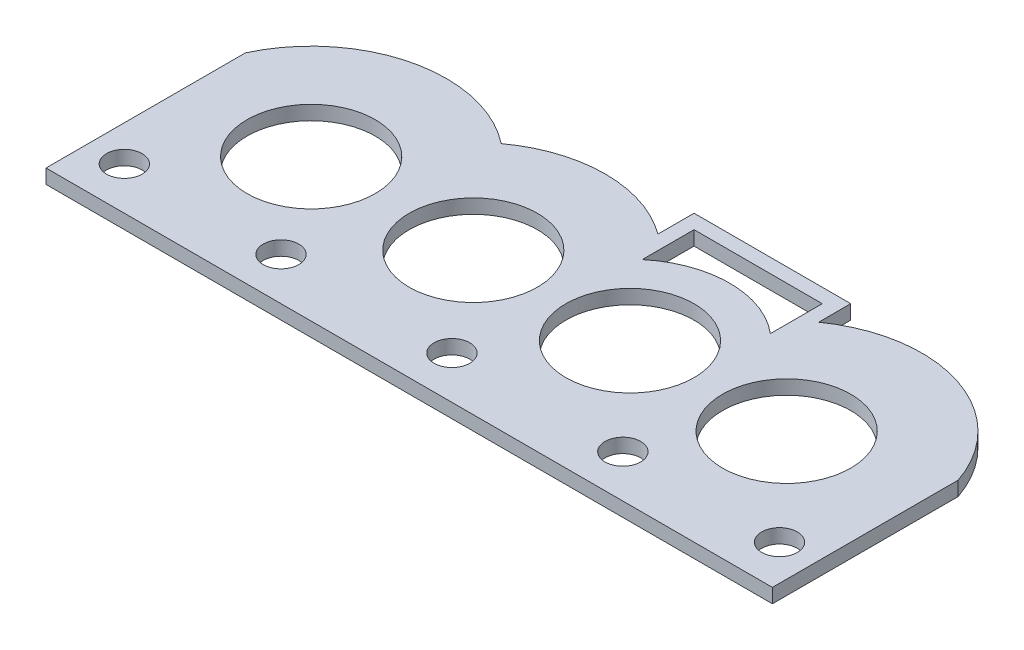
SolidWorks part; units mm, degrees
ref_plane "Front Plane" through (0, 0, 0) normal (0, 0, 1) x (1, 0, 0)
ref_plane "Top Plane" through (0, 0, 0) normal (0, 1, 0) x (1, 0, 0)
ref_plane "Right Plane" through (0, 0, 0) normal (1, 0, 0) x (0, 0, -1)
sketch "Sketch1" plane through (0, 0, 0) normal (0, 1, 0) x (1, 0, 0)
  line L0 (48.5, 3) -> (2.5, 3) construction
  line L1 (0, 0) -> (51, 0) construction
  line L2 (0, 0) -> (0, 14) construction
  line L3 (25.5, 20) -> (36.5, 20) construction
  line L4 (51, 0) -> (51, 13.0414) construction
  line L5 (25.5, 20) -> (36.5, 20)
  line L6 (0, 14) -> (0, 0)
  line L7 (0, 0) -> (51, 0)
  line L8 (51, 13.0414) -> (51, 0)
  line L9 (1.9337, 10) -> (51, 10) construction
  line L10 (35.5, 19) -> (35.5, 15.3619)
  line L12 (25.5, 17.4618) -> (25.5, 20)
  line L13 (25.5, 20) -> (36.5, 20)
  line L14 (36.5, 17.746) -> (36.5, 20)
  line L15 (25.5, 19) -> (36.5, 19) construction
  line L16 (50, 12.8723) -> (50, 1) construction
  line L17 (26.5, 15.1126) -> (26.5, 20) construction
  line L18 (26.5, 15.3619) -> (26.5, 19)
  line L19 (26.5, 19) -> (35.5, 19)
  line L20 (1, 1) -> (50, 1) construction
  line L21 (1, 13.7728) -> (1, 1) construction
  line L22 (35.5, 15.4772) -> (35.5, 20) construction
  circle A0 centre (8.6168, 10) radius 4.5
  circle A1 centre (20, 10) radius 4.5
  circle A2 centre (31, 10) radius 4.5
  circle A3 centre (42, 10) radius 4.5
  arc A7 (51, 13.0414) -> (36.5, 17.746) centre (42, 10) ccw
  arc A9 (25.5, 17.4618) -> (14.4982, 17.4605) centre (20, 10) ccw
  circle A10 centre (2.5, 3) radius 1.25
  circle A11 centre (42, 10) radius 9.5 construction
  circle A12 centre (13.5, 3) radius 1.25
  arc A13 (14.4982, 17.4605) -> (0, 14) centre (8.6168, 10) ccw
  circle A14 centre (25.5, 3) radius 1.25
  circle A15 centre (37.5, 3) radius 1.25
  circle A16 centre (48.5, 3) radius 1.25
  arc A18 (35.5, 15.3619) -> (26.5, 15.3619) centre (31, 10) ccw
  arc A19 (26.5, 15.1126) -> (14.478, 16.156) centre (20, 10) ccw construction
  arc A21 (14.478, 16.156) -> (1, 13.7728) centre (8.6168, 10) ccw construction
  arc A23 (50, 12.8723) -> (35.5, 15.4772) centre (42, 10) ccw construction
  dimension "D3" = 4.5
  dimension "D4" = 9
  dimension "D5" = 9
  dimension "D6" = 9
  dimension "D11" = 5
  dimension "D12" = 14.4982
  dimension "D16" = 14
  dimension "D2" = 10
  dimension "D18" = 2.5
  dimension "D19" = 2.5
  dimension "D20" = 2.5
  dimension "D21" = 2.5
  dimension "D22" = 2.5
  dimension "D31" = 7
  dimension "D1" = 51
  dimension "D7" = 9
  dimension "D8" = 20
  dimension "D9" = 20
  dimension "D10" = 20
  dimension "D13" = 25.5
  dimension "D15" = 14.5
  dimension "D17" = 3
  dimension "D23" = 2.5
  dimension "D24" = 11
  dimension "D25" = 12
  dimension "D26" = 12
  dimension "D27" = 11
  dimension "D30" = 1
  dimension "D14" = 5
  dimension "D29" = 1
extrude "Boss-Extrude1" add sketch "Sketch1" along normal blind 1 contours A9 A13 L6 L7 L8 A7 L14 L5 L12 A16 A15 A14 A0 A1 A2 A3 A10 A12 L10 A18 L18 L19
